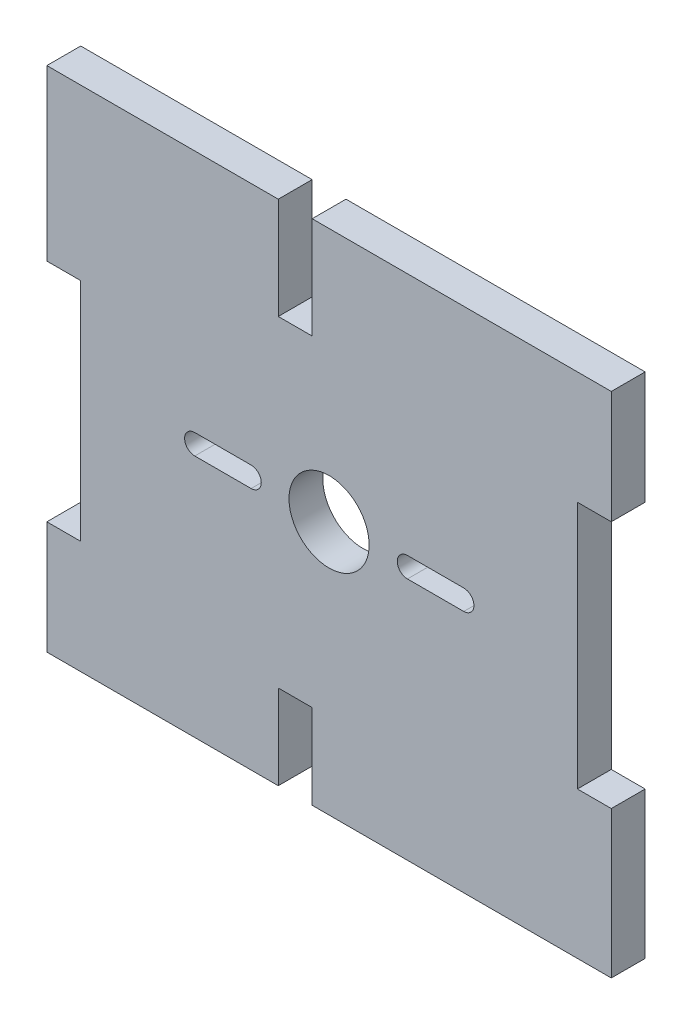
SolidWorks part; units mm, degrees
ref_plane "前视基准面" through (0, 0, 0) normal (0, 0, 1) x (1, 0, 0)
ref_plane "上视基准面" through (0, 0, 0) normal (0, 1, 0) x (1, 0, 0)
ref_plane "右视基准面" through (0, 0, 0) normal (1, 0, 0) x (0, 0, -1)
ref_plane "基准面1" through (0, 0, 3) normal (0, 0, 1) x (1, 0, 0)
sketch "草图1" plane through (0, 0, 3) normal (0, 0, 1) x (1, 0, 0)
  line L0 (28.0745, 23.3866) -> (33.0644, 23.3866)
  line L1 (33.0644, 21.5871) -> (28.0745, 21.5871)
  line L2 (19.6324, 35.9998) -> (16.6324, 35.9998)
  line L3 (16.6324, 35.9998) -> (16.6324, 44.9999)
  line L4 (16.6324, 44.9999) -> (-3.8674, 44.9999)
  line L5 (-3.8674, 44.9999) -> (-3.8674, 29.9998)
  line L6 (-3.8674, 29.9998) -> (-0.8673, 29.9998)
  line L7 (-0.8673, 29.9998) -> (-0.8673, 9.9991)
  line L8 (-0.8673, 9.9991) -> (-3.8674, 9.9991)
  line L9 (-3.8674, 9.9991) -> (-3.8674, 0)
  line L10 (-3.8674, 0) -> (16.6324, 0)
  line L11 (16.6324, 0) -> (16.6324, 7.4993)
  line L12 (16.6324, 7.4993) -> (19.6324, 7.4993)
  line L13 (19.6324, 7.4993) -> (19.6324, 0)
  line L14 (19.6324, 0) -> (46.1319, 0)
  line L15 (46.1319, 0) -> (46.1319, 13.0005)
  line L16 (46.1319, 13.0005) -> (43.1319, 13.0005)
  line L17 (43.1319, 13.0005) -> (43.1319, 34.9994)
  line L18 (43.1319, 34.9994) -> (46.1319, 34.9994)
  line L19 (46.1319, 34.9994) -> (46.1319, 44.9999)
  line L20 (46.1319, 44.9999) -> (19.6324, 44.9999)
  line L21 (19.6324, 44.9999) -> (19.6324, 35.9998)
  line L22 (14.2266, 21.5995) -> (9.2367, 21.5995)
  line L23 (9.2367, 23.399) -> (14.2266, 23.399)
  circle A0 centre (21.1317, 22.4992) radius 3.55
  arc A1 (28.0745, 21.5871) -> (28.0745, 23.3866) centre (28.0745, 22.4869) cw
  arc A2 (33.0644, 23.3866) -> (33.0644, 21.5871) centre (33.0644, 22.4869) cw
  arc A3 (9.2367, 21.5995) -> (9.2367, 23.399) centre (9.2367, 22.4992) cw
  arc A4 (14.2266, 23.399) -> (14.2266, 21.5995) centre (14.2266, 22.4992) cw
extrude "凸台-拉伸1" add sketch "草图1" against normal blind 3
